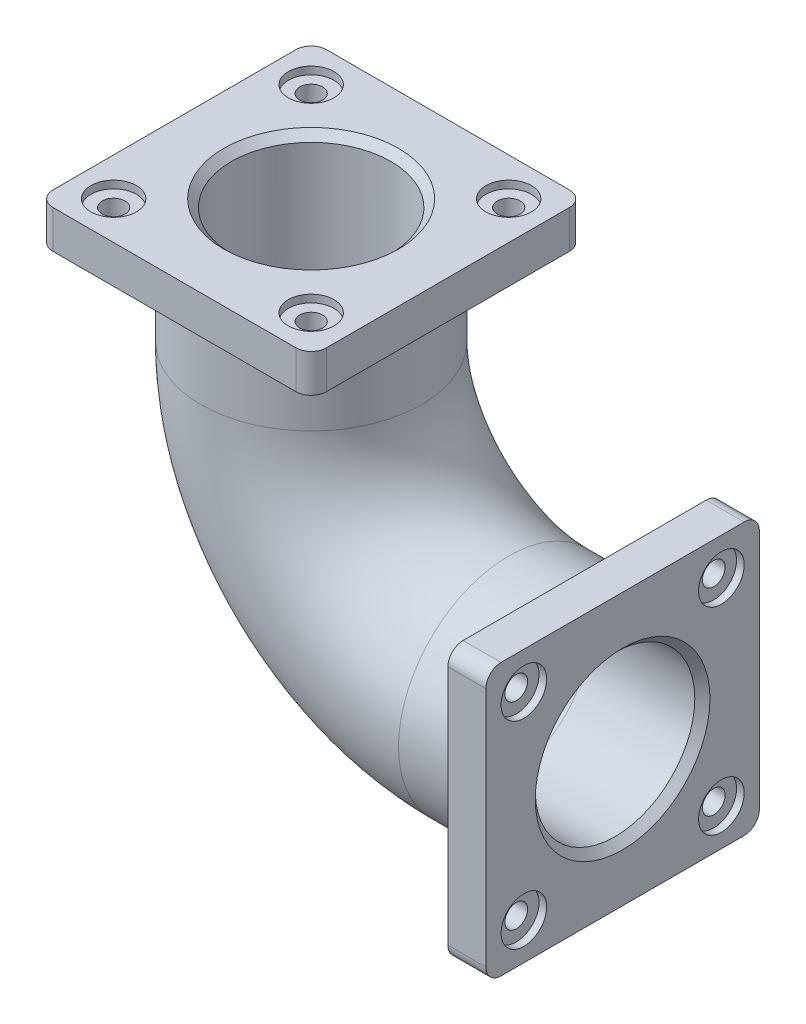
SolidWorks part; units mm, degrees
ref_plane "Piano frontale" through (0, 0, 0) normal (0, 0, 1) x (1, 0, 0)
ref_plane "Piano superiore" through (0, 0, 0) normal (0, 1, 0) x (1, 0, 0)
ref_plane "Piano destro" through (0, 0, 0) normal (1, 0, 0) x (0, 0, -1)
sketch "Schizzo1" plane through (0, 0, 0) normal (0, 0, 1) x (1, 0, 0)
  line L0 (0, 0) -> (-150, 0)
  line L1 (-410, 260) -> (-410, 422.3384)
  arc A0 (-150, 0) -> (-410, 260) centre (-150, 260) cw
  dimension "D2" = 260
  dimension "D1" = 150
sketch "Schizzo2" plane through (0, 0, 0) normal (1, 0, 0) x (0, 0, -1)
  circle A0 centre (0, 0) radius 145
  dimension "D1" = 290
sweep "Sweep-Sottile1" add profiles "Schizzo2" path "Schizzo1" parameters "D1"=40
sketch "Schizzo5" plane through (0, 0, 0) normal (1, 0, 0) x (0, 0, -1)
  line L1 (-180, -178.7342) -> (180, -178.7342)
  line L2 (-180, -178.7342) -> (-180, 178.7342)
  line L3 (-180, 178.7342) -> (180, 178.7342)
  line L4 (180, -178.7342) -> (180, 178.7342)
  line L5 (-180, -178.7342) -> (180, 178.7342) construction
  line L6 (-180, 178.7342) -> (180, -178.7342) construction
  point P0 (0, 0)
  point P6 (0, 0)
  dimension "D1" = 360
  dimension "D2" = 357.4683
extrude "Estrusione-Estrusione2" add sketch "Schizzo5" against normal blind 50 contours L1 L4 L3 L2
fillet "Raccordo2" radius 20 4 edges at (-25, -178.7342, -180) (-25, -178.7342, 180) (-25, 178.7342, -180) (-25, 178.7342, 180)
sketch "Schizzo11" plane through (0, 422.3384, 0) normal (0, 1, 0) x (1, 0, 0)
  line L0 (-410, 0) -> (-150, 0) construction
  line L1 (-570, -180) -> (-250, -180)
  line L2 (-590, -160) -> (-590, 160)
  line L3 (-570, 180) -> (-250, 180)
  line L4 (-230, -160) -> (-230, 160)
  line L5 (-590, -180) -> (-230, 180) construction
  line L6 (-590, 180) -> (-230, -180) construction
  arc A0 (-570, -180) -> (-590, -160) centre (-570, -160) cw
  arc A1 (-590, 160) -> (-570, 180) centre (-570, 160) cw
  arc A2 (-250, -180) -> (-230, -160) centre (-250, -160) ccw
  arc A3 (-250, 180) -> (-230, 160) centre (-250, 160) cw
  point P0 (-410, 0)
  circle M6 centre (-410, 0) radius 145
  dimension "D3" = 20
  dimension "D1" = 360
  dimension "D2" = 360
extrude "Estrusione-Estrusione3" add sketch "Schizzo11" against normal blind 50 contours A3 L3 A1 L2 A0 L1 A2 L4 M6
sketch "Schizzo12" plane through (0, 0, 0) normal (1, 0, 0) x (0, 0, -1)
  line L1 (-130, -130) -> (130, -130) construction
  line L2 (-130, -130) -> (-130, 130) construction
  line L3 (-130, 130) -> (130, 130) construction
  line L4 (130, -130) -> (130, 130) construction
  line L5 (-130, -130) -> (130, 130) construction
  line L6 (-130, 130) -> (130, -130) construction
  circle A0 centre (-130, 130) radius 30
  point P0 (0, 0)
  dimension "D1" = 60
  dimension "D2" = 260
  dimension "D3" = 260
extrude "Taglio-Estrusione1" cut sketch "Schizzo12" against normal blind 10 contours A0
sketch "Schizzo13" plane through (-10, 0, 0) normal (1, 0, 0) x (0, 0, -1)
  circle A0 centre (-130, 130) radius 15
  dimension "D1" = 30
extrude "Taglio-Estrusione2" cut sketch "Schizzo13" against normal up to next
pattern_circular "RipetizioneCircolare1" count 4 over 360 about axis through (0, 0, 0) along (1, 0, 0) of "Taglio-Estrusione2", "Taglio-Estrusione1"
sketch "Schizzo14" plane through (0, 422.3384, 0) normal (0, 1, 0) x (1, 0, 0)
  line L0 (-410, 0) -> (-150, 0) construction
  line L1 (-540, -130) -> (-280, -130) construction
  line L2 (-540, -130) -> (-540, 130) construction
  line L3 (-540, 130) -> (-280, 130) construction
  line L4 (-280, -130) -> (-280, 130) construction
  line L5 (-540, -130) -> (-280, 130) construction
  line L6 (-540, 130) -> (-280, -130) construction
  circle A0 centre (-540, 130) radius 30
  point P0 (-410, 0)
  dimension "D3" = 60
  dimension "D1" = 260
  dimension "D2" = 260
extrude "Taglio-Estrusione3" cut sketch "Schizzo14" against normal blind 10 contours A0
sketch "Schizzo16" plane through (0, 412.3384, 0) normal (0, 1, 0) x (1, 0, 0)
  circle A0 centre (-540, 130) radius 15
  circle A1 centre (-540, 130) radius 30 construction
  point P2 (0, 0)
  dimension "D1" = 30
extrude "Taglio-Estrusione4" cut sketch "Schizzo16" against normal up to next contours A0
pattern_circular "RipetizioneCircolare2" count 4 over 360 about axis through (-410, 0, 0) along (0, 1, 0) of "Taglio-Estrusione4", "Taglio-Estrusione3"
chamfer "Smusso1" distance 10 angle 45 2 edges at (0, 0, -105) (-410, 422.3384, -105)
